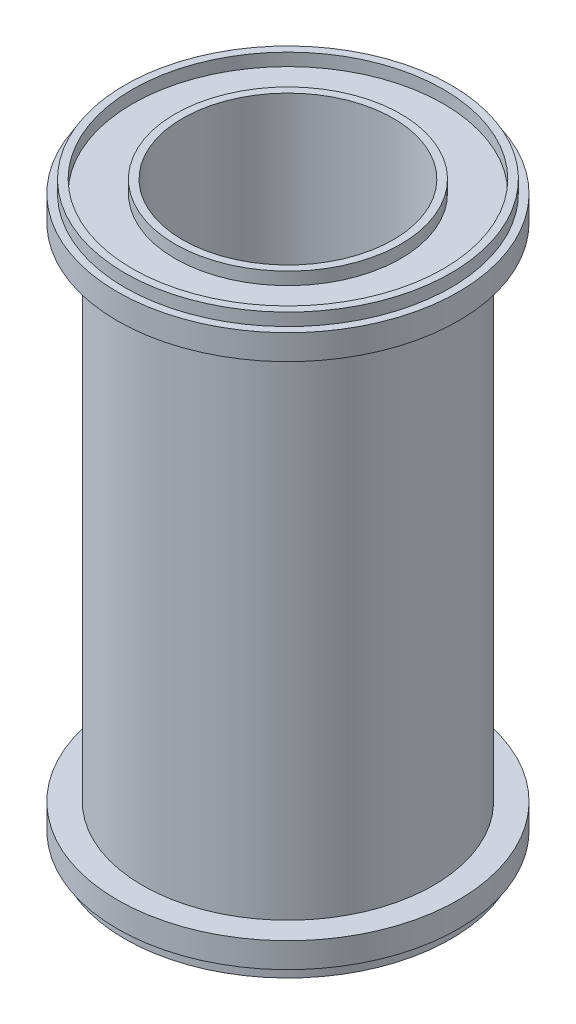
SolidWorks part; units mm, degrees
ref_plane "Front" through (0, 0, 0) normal (0, 0, 1) x (1, 0, 0)
ref_plane "Top" through (0, 0, 0) normal (0, 1, 0) x (1, 0, 0)
ref_plane "Right" through (0, 0, 0) normal (1, 0, 0) x (0, 0, -1)
ref_plane "Plane1" through (0, 0, 0) normal (0, -1, 0) x (1, 0, 0)
sketch "Sketch1" plane through (0, 0, 0) normal (1, 0, 0) x (0, 1, 0)
  line L0 (11.5, 4.5) -> (11.5, 4.2)
  line L1 (11, 4.5) -> (11.5, 4.5)
  line L2 (11, 6.2) -> (11, 4.5)
  line L3 (11.5, 6.2) -> (11, 6.2)
  line L4 (11.5, 6.5) -> (11.5, 6.2)
  line L5 (11, 6.5) -> (11.5, 6.5)
  line L6 (11, 6.8) -> (11, 6.5)
  line L7 (10, 6.8) -> (11, 6.8)
  line L8 (10, 5.8) -> (10, 6.8)
  line L9 (10, 5.8) -> (-10, 5.8)
  line L10 (-10, 5.8) -> (-10, 6.8)
  line L11 (-10, 6.8) -> (-11, 6.8)
  line L12 (-11, 6.8) -> (-11, 6.5)
  line L13 (-11, 6.5) -> (-11.5, 6.5)
  line L14 (-11.5, 6.5) -> (-11.5, 6.2)
  line L15 (-11.5, 6.2) -> (-11, 6.2)
  line L16 (-11, 6.2) -> (-11, 4.5)
  line L17 (-11, 4.5) -> (-11.5, 4.5)
  line L18 (-11.5, 4.5) -> (-11.5, 4.2)
  line L19 (-11.5, 4.2) -> (11.5, 4.2)
  line L20 (0, 0) -> (11.5, 0) construction
  line L21 (0, 0) -> (0, 8.7484) construction
  dimension "D1" = 8.4
  dimension "D2" = 11.6
  dimension "D3" = 23
  dimension "D4" = 0.5
  dimension "D5" = 1
  dimension "D6" = 13.6
  dimension "D7" = 0.3
  dimension "D8" = 1.7
revolve "Revolve1" add sketch "Sketch1" angle 360 about L20
